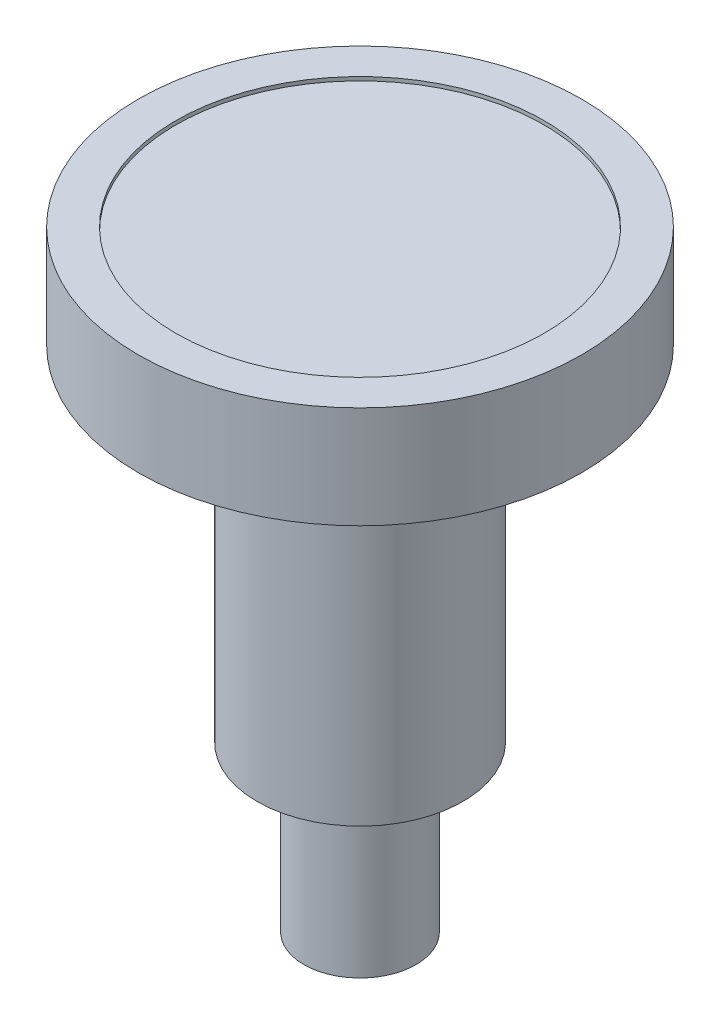
SolidWorks part; units mm, degrees
ref_plane "Front Plane" through (0, 0, 0) normal (0, 0, 1) x (1, 0, 0)
ref_plane "Top Plane" through (0, 0, 0) normal (0, 1, 0) x (1, 0, 0)
ref_plane "Right Plane" through (0, 0, 0) normal (1, 0, 0) x (0, 0, -1)
sketch "Sketch1" plane through (0, 0, 0) normal (0, 1, 0) x (1, 0, 0)
  circle A0 centre (0, 0) radius 1.5
  dimension "D1" = 3
extrude "Boss-Extrude1" add sketch "Sketch1" along normal blind 4.4
sketch "Sketch2" plane through (0, 4.4, 0) normal (0, 1, 0) x (1, 0, 0)
  circle A0 centre (0, 0) radius 2.75
  dimension "D1" = 5.5
extrude "Boss-Extrude2" add sketch "Sketch2" along normal blind 9.2
sketch "Sketch3" plane through (0, 13.6, 0) normal (0, 1, 0) x (1, 0, 0)
  circle A0 centre (0, 0) radius 5.925
  dimension "D1" = 11.85
extrude "Boss-Extrude3" add sketch "Sketch3" along normal blind 2.73
fillet "Fillet1" radius 0.5 1 edges at (0, 13.6, 2.75)
sketch "Sketch4" plane through (0, 16.33, 0) normal (0, 1, 0) x (1, 0, 0)
  circle A2 centre (0, 0) radius 4.925
  circle A3 centre (0, 0) radius 4.925
  dimension "D1" = 1
extrude "Cut-Extrude1" cut sketch "Sketch4" against normal blind 0.1
